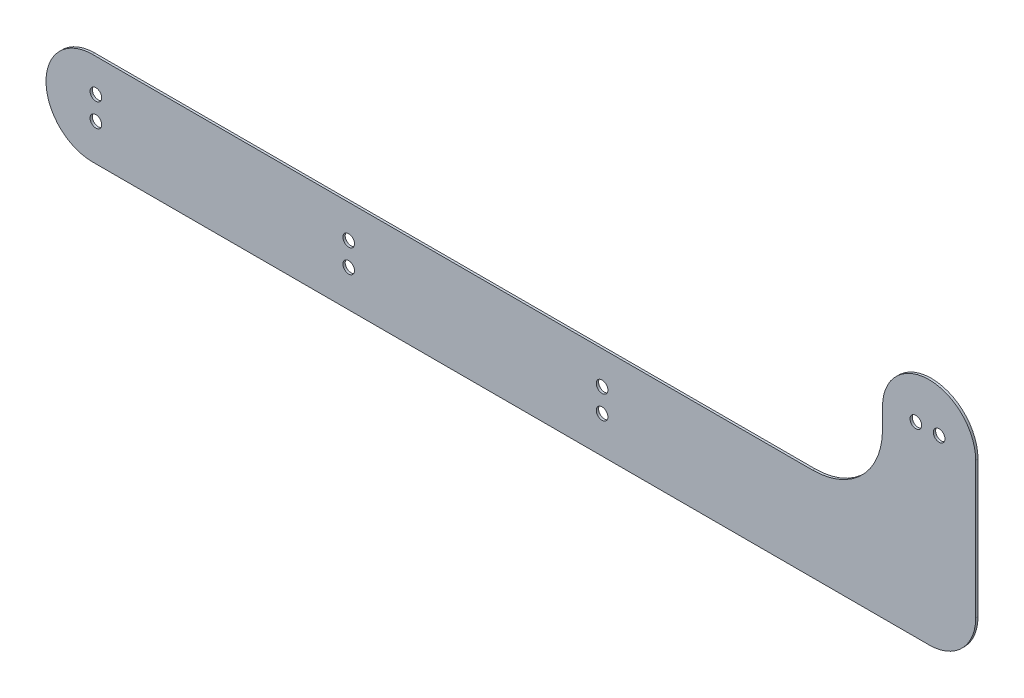
SolidWorks part; units mm, degrees
ref_plane "Front Plane" through (0, 0, 0) normal (0, 0, 1) x (1, 0, 0)
ref_plane "Top Plane" through (0, 0, 0) normal (0, 1, 0) x (1, 0, 0)
ref_plane "Right Plane" through (0, 0, 0) normal (1, 0, 0) x (0, 0, -1)
sketch "Sketch1" plane through (0, 0, 0) normal (0, 0, 1) x (1, 0, 0)
  line L3 (83.712, 32.2716) -> (392.8073, 32.2716)
  line L4 (83.712, -7.7284) -> (442.8073, -7.7284)
  line L6 (422.8073, 62.2716) -> (422.8073, 70.9)
  line L7 (462.8073, 12.2716) -> (462.8073, 70.9)
  arc A0 (83.712, 32.2716) -> (83.712, -7.7284) centre (83.712, 12.2716) ccw
  arc A1 (442.8073, -7.7284) -> (462.8073, 12.2716) centre (442.8073, 12.2716) ccw
  arc A2 (442.8073, -7.7284) -> (462.8073, 12.2716) centre (442.8073, 12.2716) ccw
  arc A3 (462.8073, 70.9) -> (422.8073, 70.9) centre (442.8073, 70.9) ccw
  arc A4 (422.8073, 62.2716) -> (392.8073, 32.2716) centre (392.8073, 62.2716) cw
  circle A5 centre (85.1299, 18.0819) radius 2.5
  circle A6 centre (85.1135, 8.0819) radius 2.5
  circle A7 centre (193.6627, 18.0819) radius 2.5
  circle A8 centre (193.6627, 8.0819) radius 2.5
  circle A9 centre (302.4265, 18.0819) radius 2.5
  circle A10 centre (302.4265, 8.0819) radius 2.5
  circle A11 centre (437.1239, 72.2993) radius 2.5
  circle A12 centre (447.1239, 72.2875) radius 2.5
  point P2 (263.2597, 12.2716)
  point P8 (442.8073, 41.5858)
  point P31 (447.1239, 72.2875)
  dimension "D1" = 30
  dimension "D2" = 5
  dimension "D3" = 5
  dimension "D4" = 10
  dimension "D5" = 5
  dimension "D6" = 5
  dimension "D7" = 10
  dimension "D8" = 5
  dimension "D9" = 5
  dimension "D10" = 5
  dimension "D11" = 5
  dimension "D12" = 10
extrude "Boss-Extrude1" add sketch "Sketch1" along normal blind 1 contours L6 A4 L3 A0 L4 A1 L7 A3 A12 A11 A10 A9 A8 A7 A6 A5
